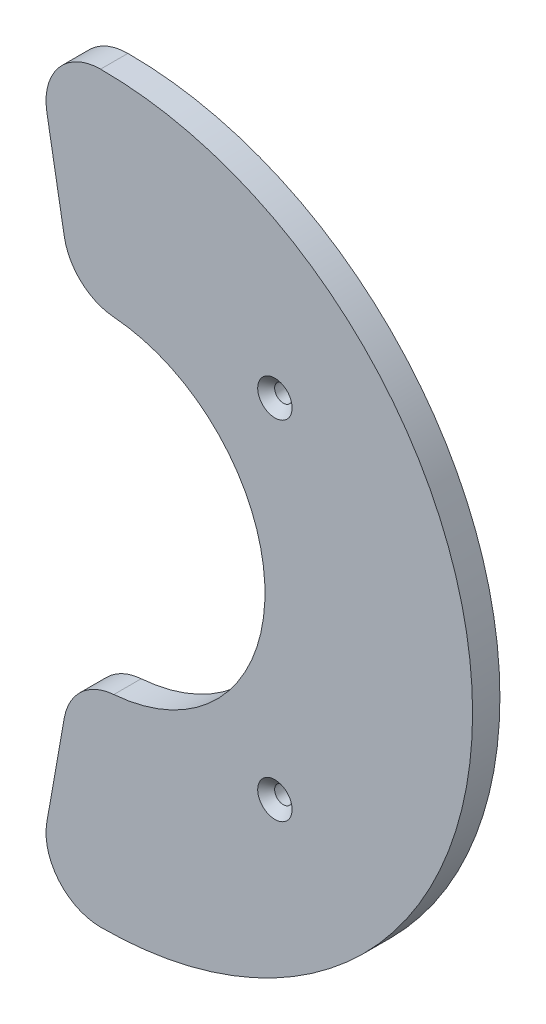
SolidWorks part; units mm, degrees
material "ﾎﾟﾘｵｷｼﾒﾁﾚﾝ(POM)ｱｾﾀｰﾙ共重合体"
ref_plane "Front Plane" through (0, 0, 0) normal (0, 0, 1) x (1, 0, 0)
ref_plane "Top Plane" through (0, 0, 0) normal (0, 1, 0) x (1, 0, 0)
ref_plane "Right Plane" through (0, 0, 0) normal (1, 0, 0) x (0, 0, -1)
sketch "ｽｹｯﾁ1" plane through (0, 0, 0) normal (0, 0, 1) x (1, 0, 0)
  line L0 (0, 0) -> (101.7909, 0) construction
  line L1 (0, 0) -> (56.5437, 56.5437) construction
  line L2 (-5.2094, 29.5442) -> (-11.8081, 66.9669)
  line L3 (-5.2094, -29.5442) -> (-11.8081, -66.9669)
  arc A0 (-11.8081, -66.9669) -> (-11.8081, 66.9669) centre (0, 0) ccw
  arc A1 (-5.2094, -29.5442) -> (-5.2094, 29.5442) centre (0, 0) ccw
  circle A2 centre (31.8198, 31.8198) radius 1.6
  circle A3 centre (31.8198, -31.8198) radius 1.6
  dimension "D1" = 136
  dimension "D2" = 60
  dimension "D3" = 3.2
  dimension "D5" = 45
  dimension "D4" = 45
  dimension "D6" = 200
extrude "ﾎﾞｽ - 押し出し1" add sketch "ｽｹｯﾁ1" along normal blind 5
fillet "ﾌｨﾚｯﾄ1" radius 10 4 edges at (-5.2094, 29.5442, 2.5) (-11.8081, 66.9669, 2.5) (-11.8081, -66.9669, 2.5) (-5.2094, -29.5442, 2.5)
hole_wizard "M3 丸皿ねじ用皿穴1" positions "ｽｹｯﾁ4" profile "ｽｹｯﾁ3" countersink size "M3" standard "JIS" end condition through all
sketch "ｽｹｯﾁ4" plane through (0, 0, 5) normal (0, 0, 1) x (1, 0, 0)
  point P0 (31.8198, 31.8198)
  point P3 (31.8198, -31.8198)
sketch "ｽｹｯﾁ3" plane through (31.8198, 31.8198, 5) normal (1, 0, 0) x (0, -1, 0)
  line L0 (0, 0) -> (0, 5)
  line L1 (0, 5) -> (1.6, 5)
  line L2 (1.6, 5) -> (1.6, 1.55)
  line L3 (1.6, 1.55) -> (3.15, 0)
  line L5 (3.15, 0) -> (0, 0)
  line L6 (-1.6, 1.55) -> (-3.15, 0) construction
  line L11 (0, -6.35) -> (0, 107.95) construction
  dimension "通し穴の直径" = 3.2
  dimension "通し穴の深さ" = 5
  dimension "表面の皿穴の直径" = 6.3
  dimension "表面の皿穴の角度" = 90
sketch "ｽｹｯﾁ5" plane through (0, 0, 0) normal (0, 0, -1) x (-1, 0, 0)
  line L0 (0, 0) -> (-100.3476, 0) construction
  circle A0 centre (-31.8198, 31.8198) radius 3
  circle A1 centre (-31.8198, -31.8198) radius 3
  dimension "D1" = 6
extrude "ｶｯﾄ - 押し出し1" cut sketch "ｽｹｯﾁ5" against normal blind 1
